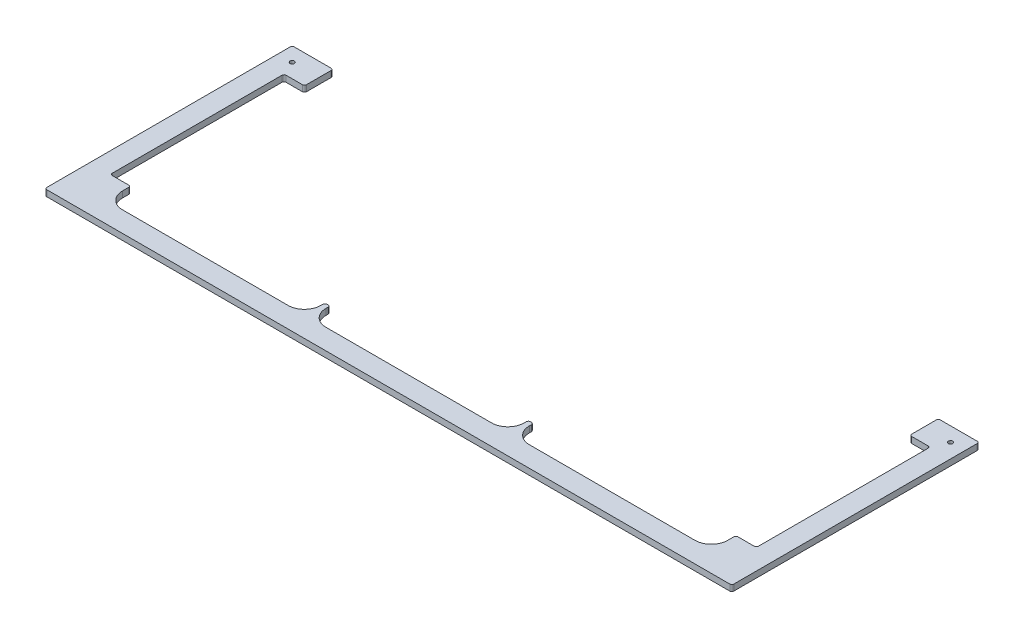
SolidWorks part; units mm, degrees
material "PC High Viscosity"
ref_plane "Front Plane" through (0, 0, 0) normal (0, 0, 1) x (1, 0, 0)
ref_plane "Top Plane" through (0, 0, 0) normal (0, 1, 0) x (1, 0, 0)
ref_plane "Right Plane" through (0, 0, 0) normal (1, 0, 0) x (0, 0, -1)
sketch "Sketch1" plane through (0, 0, 0) normal (0, 1, 0) x (1, 0, 0)
  line L42 (1006.475, 384.175) -> (1063.625, 384.175)
  line L43 (3.175, 0) -> (1063.625, 0)
  line L44 (0, 3.175) -> (0, 381)
  line L45 (3.175, 384.175) -> (60.325, 384.175)
  line L46 (1066.8, 3.175) -> (1066.8, 381)
  line L48 (63.5, 381) -> (63.5, 342.9)
  line L49 (88.9, 31.75) -> (346.075, 31.75)
  line L50 (1003.3, 381) -> (1003.3, 342.9)
  line L51 (404.8125, 31.75) -> (661.9875, 31.75)
  line L53 (379.4125, 57.15) -> (379.4125, 60.325)
  line L54 (376.2375, 63.5) -> (374.65, 63.5)
  line L55 (371.475, 57.15) -> (371.475, 60.325)
  line L57 (695.325, 57.15) -> (695.325, 60.325)
  line L58 (692.15, 63.5) -> (690.5625, 63.5)
  line L59 (687.3875, 57.15) -> (687.3875, 60.325)
  line L60 (720.725, 31.75) -> (977.9, 31.75)
  line L61 (63.5, 66.675) -> (63.5, 57.15)
  line L62 (60.325, 339.725) -> (34.925, 339.725)
  line L64 (60.325, 69.85) -> (34.925, 69.85)
  line L65 (31.75, 336.55) -> (31.75, 73.025)
  line L66 (1003.3, 66.675) -> (1003.3, 57.15)
  line L67 (1006.475, 339.725) -> (1031.875, 339.725)
  line L69 (1006.475, 69.85) -> (1031.875, 69.85)
  line L70 (1035.05, 336.55) -> (1035.05, 73.025)
  circle A12 centre (22.225, 361.95) radius 3.3734
  circle A13 centre (1044.575, 361.95) radius 3.3734
  arc A14 (977.9, 31.75) -> (1003.3, 57.15) centre (977.9, 57.15) ccw
  arc A15 (720.725, 31.75) -> (695.325, 57.15) centre (720.725, 57.15) cw
  arc A16 (661.9875, 31.75) -> (687.3875, 57.15) centre (661.9875, 57.15) ccw
  arc A17 (404.8125, 31.75) -> (379.4125, 57.15) centre (404.8125, 57.15) cw
  arc A18 (346.075, 31.75) -> (371.475, 57.15) centre (346.075, 57.15) ccw
  arc A19 (63.5, 57.15) -> (88.9, 31.75) centre (88.9, 57.15) ccw
  arc A20 (1031.875, 339.725) -> (1035.05, 336.55) centre (1031.875, 336.55) cw
  arc A21 (1006.475, 339.725) -> (1003.3, 342.9) centre (1006.475, 342.9) cw
  arc A22 (1031.875, 69.85) -> (1035.05, 73.025) centre (1031.875, 73.025) ccw
  arc A23 (1003.3, 66.675) -> (1006.475, 69.85) centre (1006.475, 66.675) cw
  arc A24 (63.5, 66.675) -> (60.325, 69.85) centre (60.325, 66.675) ccw
  arc A25 (34.925, 69.85) -> (31.75, 73.025) centre (34.925, 73.025) cw
  arc A26 (34.925, 339.725) -> (31.75, 336.55) centre (34.925, 336.55) ccw
  arc A27 (60.325, 339.725) -> (63.5, 342.9) centre (60.325, 342.9) ccw
  arc A28 (1063.625, 384.175) -> (1066.8, 381) centre (1063.625, 381) cw
  arc A29 (1006.475, 384.175) -> (1003.3, 381) centre (1006.475, 381) ccw
  arc A30 (1063.625, 0) -> (1066.8, 3.175) centre (1063.625, 3.175) ccw
  arc A31 (695.325, 60.325) -> (692.15, 63.5) centre (692.15, 60.325) ccw
  arc A32 (690.5625, 63.5) -> (687.3875, 60.325) centre (690.5625, 60.325) ccw
  arc A33 (379.4125, 60.325) -> (376.2375, 63.5) centre (376.2375, 60.325) ccw
  arc A34 (374.65, 63.5) -> (371.475, 60.325) centre (374.65, 60.325) ccw
  arc A35 (60.325, 384.175) -> (63.5, 381) centre (60.325, 381) cw
  arc A36 (0, 381) -> (3.175, 384.175) centre (3.175, 381) cw
  arc A37 (3.175, 0) -> (0, 3.175) centre (3.175, 3.175) cw
  point P25 (695.325, 31.75)
  point P30 (379.4125, 31.75)
  point P45 (1035.05, 339.725)
  point P48 (1003.3, 339.725)
  point P51 (1035.05, 69.85)
  point P58 (31.75, 69.85)
  point P61 (31.75, 339.725)
  point P64 (63.5, 339.725)
  point P67 (1066.8, 384.175)
  point P70 (1003.3, 384.175)
  point P75 (695.325, 63.5)
  point P78 (687.3875, 63.5)
  point P81 (379.4125, 63.5)
  point P84 (371.475, 63.5)
  point P91 (0, 0)
  dimension "D10" = 63.5
  dimension "D12" = 22.225
  dimension "D16" = 22.225
  dimension "D19" = 44.45
  dimension "D14" = 6.7469
  dimension "D15" = 6.7469
  dimension "D18" = 25.4
  dimension "D25" = 3.175
  dimension "D26" = 3.175
  dimension "D1" = 307.975
  dimension "D2" = 63.5
  dimension "D3" = 307.975
  dimension "D4" = 307.975
  dimension "D5" = 31.75
  dimension "D6" = 7.9375
  dimension "D7" = 7.9375
  dimension "D8" = 63.5
  dimension "D9" = 63.5
  dimension "D11" = 384.175
  dimension "D13" = 22.225
  dimension "D17" = 22.225
  dimension "D20" = 38.1
  dimension "D21" = 31.75
  dimension "D22" = 38.1
  dimension "D23" = 44.45
  dimension "D24" = 31.75
extrude "Boss-Extrude1" add sketch "Sketch1" along normal blind 9.525
